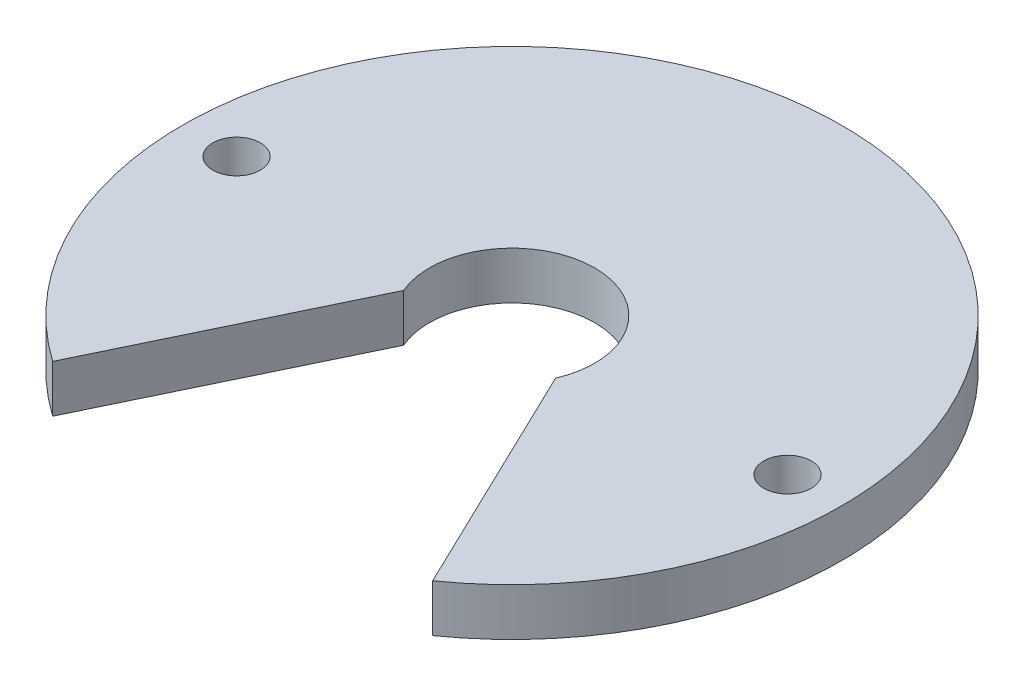
SolidWorks part; units mm, degrees
material "Custom Plastic"
ref_plane "Front Plane" through (0, 0, 0) normal (0, 0, 1) x (1, 0, 0)
ref_plane "Top Plane" through (0, 0, 0) normal (0, 1, 0) x (1, 0, 0)
ref_plane "Right Plane" through (0, 0, 0) normal (1, 0, 0) x (0, 0, -1)
sketch "Sketch1" plane through (0, 0, 0) normal (0, 1, 0) x (1, 0, 0)
  circle A0 centre (0, 0) radius 17.35
  dimension "D1" = 34.7
extrude "Boss-Extrude1" add sketch "Sketch1" along normal blind 2.5
sketch "Sketch2" plane through (0, 2.5, 0) normal (0, 1, 0) x (1, 0, 0)
  circle A0 centre (0, 0) radius 4.35
  dimension "D1" = 8.7
extrude "Cut-Extrude1" cut sketch "Sketch2" against normal through all
sketch "Sketch3" plane through (0, 2.5, 0) normal (0, 1, 0) x (1, 0, 0)
  circle A0 centre (-14.5, 0) radius 1.25
  circle A1 centre (14.5, 0) radius 1.25
  dimension "D1" = 2.5
  dimension "D2" = 2.5
  dimension "D3" = 14.5
  dimension "D4" = 14.5
extrude "Cut-Extrude2" cut sketch "Sketch3" against normal through all
sketch "Sketch4" plane through (0, 2.5, 0) normal (0, 1, 0) x (1, 0, 0)
  line L0 (-4, -1.7095) -> (-10, -14.1782)
  line L1 (4, -1.7095) -> (10, -14.1782)
  circle A0 centre (0, 0) radius 4.35 construction
  circle A1 centre (0, 0) radius 17.35 construction
  arc A3 (-4, -1.7095) -> (4, -1.7095) centre (0, 0) ccw
  arc A4 (-10, -14.1782) -> (10, -14.1782) centre (0, 0) ccw
  dimension "D1" = 4
  dimension "D2" = 10
  dimension "D3" = 4
  dimension "D4" = 10
extrude "Cut-Extrude3" cut sketch "Sketch4" against normal through all
